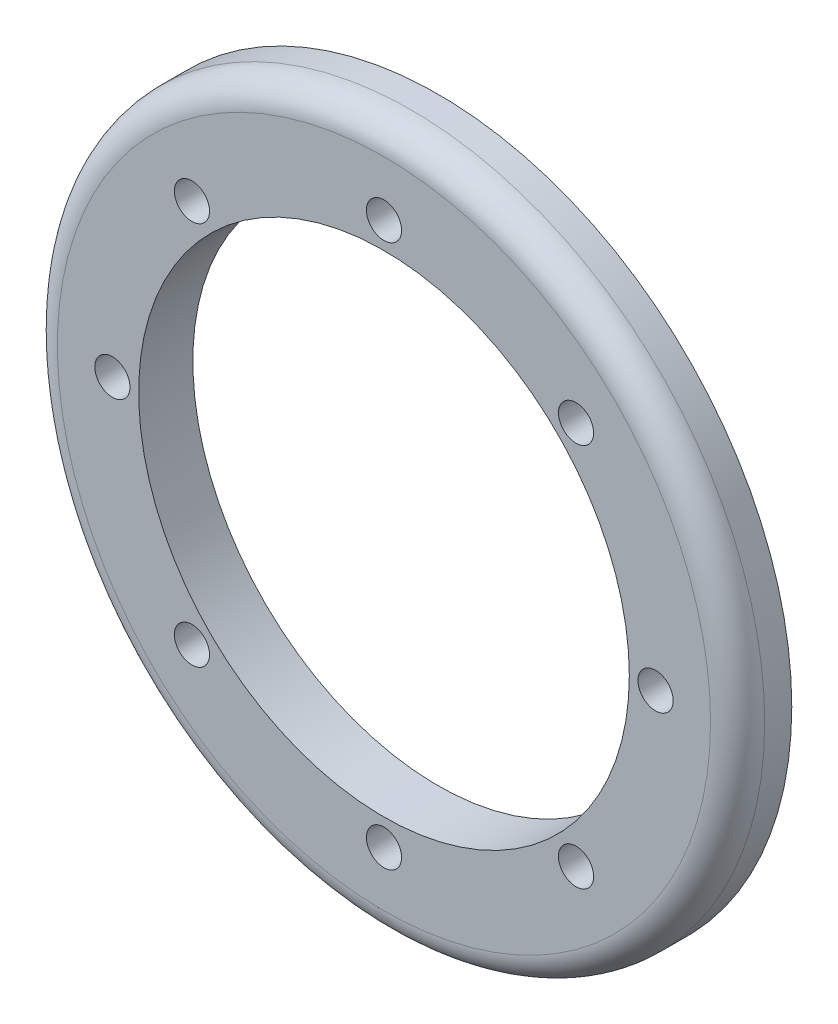
SolidWorks part; units mm, degrees
ref_plane "Front Plane" through (0, 0, 0) normal (0, 0, 1) x (1, 0, 0)
ref_plane "Top Plane" through (0, 0, 0) normal (0, 1, 0) x (1, 0, 0)
ref_plane "Right Plane" through (0, 0, 0) normal (1, 0, 0) x (0, 0, -1)
sketch "Sketch1" plane through (0, 0, 0) normal (0, 0, 1) x (1, 0, 0)
  circle A0 centre (0, 0) radius 45.3 construction
  circle A1 centre (0, 0) radius 45.3
  circle A2 centre (0, 0) radius 65.3
  circle A3 centre (35.4614, -35.4614) radius 1.65
  circle A7 centre (0, -50.15) radius 1.65
  circle A8 centre (-35.4614, -35.4614) radius 1.65
  circle A9 centre (-50.15, 0) radius 1.65
  circle A10 centre (-35.4614, 35.4614) radius 1.65
  circle A11 centre (0, 50.15) radius 1.65
  circle A12 centre (35.4614, 35.4614) radius 1.65
  circle A13 centre (50.15, 0) radius 1.65
  point P25 (0, 0)
  dimension "D2" = 3.3
  dimension "D1" = 20
  dimension "D3" = 8
extrude "Boss-Extrude1" add sketch "Sketch1" along normal blind 10
fillet "Fillet1" radius 5 1 edges at (65.3, 0, 10)
sketch "Sketch2" plane through (0, 0, 10) normal (0, 0, 1) x (1, 0, 0)
  circle A0 centre (-50.15, 0) radius 3.25
  circle A1 centre (-35.4614, -35.4614) radius 3.25
  circle A2 centre (-35.4614, 35.4614) radius 3.25
  circle A3 centre (0, 50.15) radius 3.25
  circle A4 centre (35.4614, 35.4614) radius 3.25
  circle A5 centre (50.15, 0) radius 3.25
  circle A6 centre (35.4614, -35.4614) radius 3.25
  circle A7 centre (0, -50.15) radius 3.25
  dimension "D1" = 6.5
extrude "Cut-Extrude1" cut sketch "Sketch2" against normal blind 6
